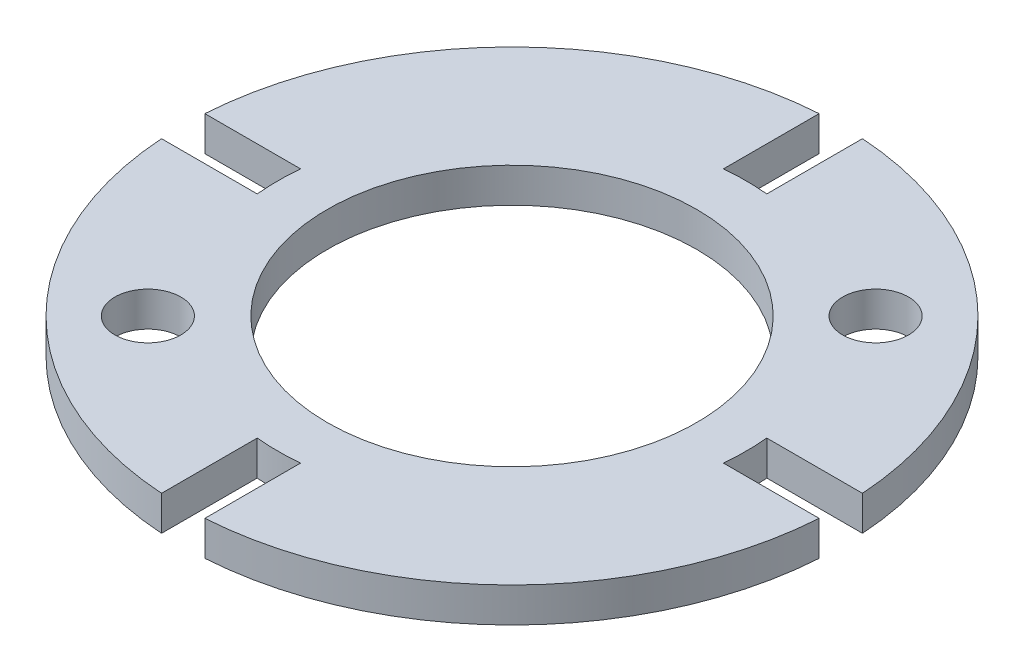
SolidWorks part; units mm, degrees
ref_plane "Front Plane" through (0, 0, 0) normal (0, 0, 1) x (1, 0, 0)
ref_plane "Top Plane" through (0, 0, 0) normal (0, 1, 0) x (1, 0, 0)
ref_plane "Right Plane" through (0, 0, 0) normal (1, 0, 0) x (0, 0, -1)
sketch "Sketch1" plane through (0, 0, 0) normal (0, 1, 0) x (1, 0, 0)
  circle A0 centre (0, 0) radius 48.26
  circle A1 centre (0, 0) radius 27.051
  dimension "D1" = 96.52
  dimension "D2" = 54.102
extrude "Boss-Extrude1" add sketch "Sketch1" along normal blind 5.08
sketch "Sketch2" plane through (0, 5.08, 0) normal (0, 1, 0) x (1, 0, 0)
  line L0 (-34.1427, 3.175) -> (-84.8851, 3.175)
  line L1 (-3.175, 55.8229) -> (3.175, 55.8229)
  line L2 (-3.175, 55.8229) -> (-3.175, 34.1427)
  line L3 (-3.175, -55.6798) -> (3.175, -55.6798)
  line L4 (3.175, 55.8229) -> (3.175, 34.1427)
  line L5 (73.0956, 3.175) -> (34.1427, 3.175)
  line L6 (73.0956, 3.175) -> (73.0956, -3.175)
  line L7 (73.0956, -3.175) -> (34.1427, -3.175)
  line L8 (-84.8851, 3.175) -> (-84.8851, -3.175)
  line L9 (-34.1427, -3.175) -> (-84.8851, -3.175)
  line L10 (-3.175, -34.1427) -> (-3.175, -55.6798)
  line L11 (3.175, -34.1427) -> (3.175, -55.6798)
  circle A1 centre (0, 0) radius 48.26 construction
  arc A3 (-48.1554, 3.175) -> (-48.1554, -3.175) centre (0, 0) ccw
  arc A4 (34.1427, -3.175) -> (34.1427, 3.175) centre (0, 0) ccw
  arc A5 (3.175, 34.1427) -> (-3.175, 34.1427) centre (0, 0) ccw
  arc A6 (-3.175, -48.1554) -> (-3.175, 48.1554) centre (0, 0) ccw
  arc A7 (-3.175, -34.1427) -> (3.175, -34.1427) centre (0, 0) ccw
  arc A8 (-34.1427, 3.175) -> (-34.1427, -3.175) centre (0, 0) ccw
  point P14 (-84.8851, 0)
  point P15 (0, 55.8229)
  circle M15 centre (0, 0) radius 48.26
  dimension "D2" = 68.58
  dimension "D1" = 6.35
extrude "Cut-Extrude1" cut sketch "Sketch2" against normal through all contours A8 L0 L9 M15 | A4 L7 L5 M15 | A7 L10 L11 M15 | A5 L4 L2 M15
sketch "Sketch3" plane through (0, 5.08, 0) normal (0, 1, 0) x (1, 0, 0)
  line L0 (-34.125, -34.125) -> (34.125, 34.125) construction
  arc A0 (-48.1554, -3.175) -> (-3.175, -48.1554) centre (0, 0) ccw construction
  arc A1 (48.1554, 3.175) -> (3.175, 48.1554) centre (0, 0) ccw construction
  circle A2 centre (-26.6653, -26.6653) radius 4.826
  circle A3 centre (26.6265, 26.6265) radius 4.826
  circle A4 centre (0, 0) radius 37.6555 construction
  dimension "D1" = 9.652
  dimension "D2" = 75.311
extrude "Cut-Extrude2" cut sketch "Sketch3" against normal through all contours A2 | A3
